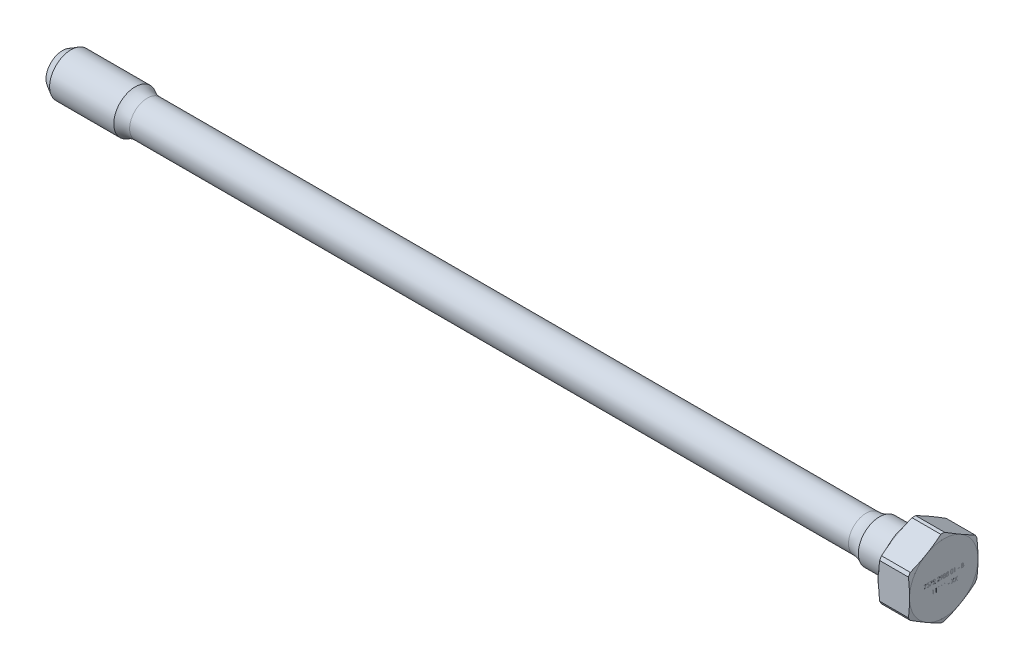
SolidWorks part; units mm, degrees
material "4340 H/T-Y"
ref_plane "Front Plane" through (0, 0, 0) normal (0, 0, 1) x (1, 0, 0)
ref_plane "Top Plane" through (0, 0, 0) normal (0, 1, 0) x (1, 0, 0)
ref_plane "Right Plane" through (0, 0, 0) normal (1, 0, 0) x (0, 0, -1)
sketch "Sketch1" plane through (0, 0, 0) normal (0, 0, 1) x (1, 0, 0)
  line L0 (8, 0) -> (6.7983, 2)
  line L1 (6.7983, 2) -> (3.4641, 2)
  line L2 (3.4641, 2) -> (0, 4)
  line L3 (0, 4) -> (0, 7.6906)
  line L4 (0, 7.6906) -> (4, 10)
  line L5 (4, 10) -> (34, 10)
  line L6 (8, 0) -> (412, 0)
  line L7 (39.6513, 8.25) -> (375.7064, 8.25)
  line L9 (382, 9.95) -> (395, 9.95)
  line L10 (397, 11.95) -> (397, 15.75)
  line L11 (397, 15.75) -> (397.5, 15.75)
  line L12 (397.5, 15.75) -> (397.5, 16)
  line L13 (397.5, 16) -> (398.0359, 18)
  line L14 (398.0359, 18) -> (411.4641, 18)
  line L15 (411.4641, 18) -> (412, 16)
  line L16 (412, 16) -> (412, 0)
  line L17 (412, 0) -> (8, 0) construction
  arc A0 (39.6513, 8.25) -> (34, 10) centre (39.6513, 18.25) cw
  arc A1 (375.7064, 8.25) -> (382, 9.95) centre (375.7064, 20.75) ccw
  arc A2 (397, 11.95) -> (395, 9.95) centre (395, 11.95) cw
  dimension "D13" = 10
  dimension "D16" = 12.5
  dimension "D23" = 2
  dimension "D1" = 412
  dimension "D2" = 0.5
  dimension "D3" = 397
  dimension "D4" = 4
  dimension "D5" = 8
  dimension "D6" = 59
  dimension "D7" = 30
  dimension "D8" = 8
  dimension "D9" = 4
  dimension "D10" = 30
  dimension "D11" = 20
  dimension "D12" = 16.5
  dimension "D14" = 34
  dimension "D15" = 19.9
  dimension "D17" = 382
  dimension "D18" = 31.5
  dimension "D19" = 36
  dimension "D20" = 32
  dimension "D21" = 15
  dimension "D22" = 75
revolve "Revolve1" add sketch "Sketch1" angle 360 about L17
cosmetic thread "Cosmetic Thread1" parameters "D2"=18
sketch "Sketch3" plane through (412, 0, 0) normal (1, 0, 0) x (0, 0, -1)
  line L1 (0, 18.4752) -> (-16, 9.2376)
  line L2 (-16, 9.2376) -> (-16, -9.2376)
  line L3 (-16, -9.2376) -> (0, -18.4752)
  line L4 (0, -18.4752) -> (16, -9.2376)
  line L5 (16, -9.2376) -> (16, 9.2376)
  line L6 (16, 9.2376) -> (0, 18.4752)
  circle A0 centre (0, 0) radius 16 construction
extrude "Cut-Extrude-Thin1" cut sketch "Sketch3" against normal up to surface (14.5 mm away) thin contours L2 L3 L4 L5 L6 L1
sketch "Sketch4" plane through (412, 0, 0) normal (-1, 0, 0) x (0, 0, -1)
  line L0 (-13.7374, 0) -> (13.8626, 0) construction
  line L1 (0, 17.7946) -> (0, -13.217) construction
  text T0 "7372 2988 01 - B\r\n 11111 - XX" font "Century Gothic" height 1.8
extrude "Cut-Extrude1" cut sketch "Sketch4" along normal blind 0.01
